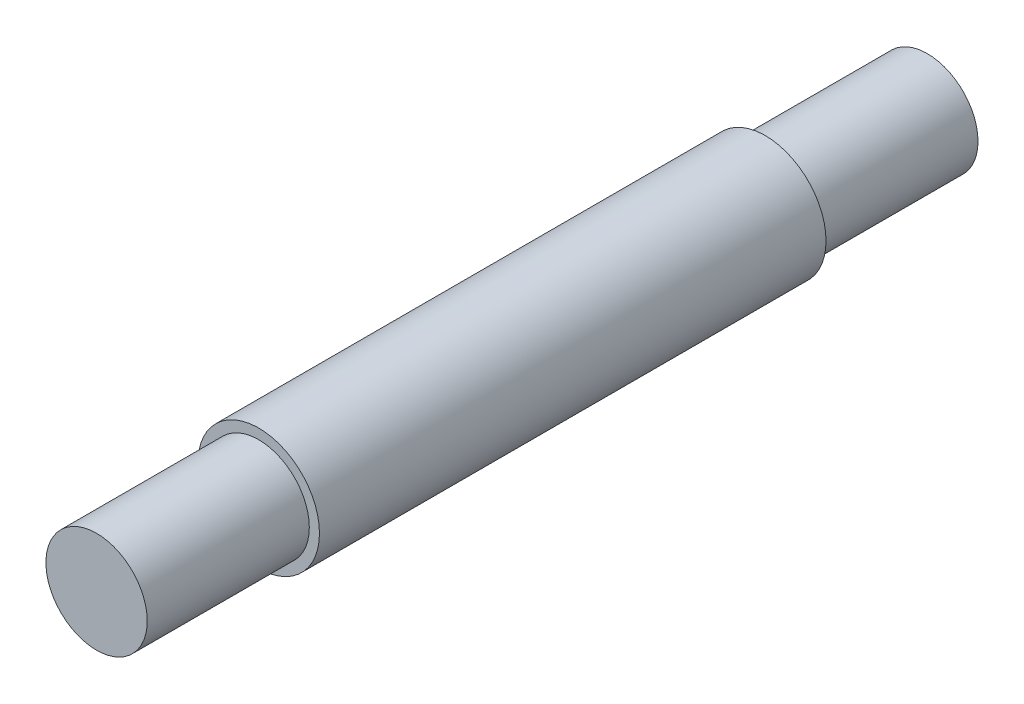
SolidWorks part; units mm, degrees
ref_plane "Ön Düzlem" through (0, 0, 0) normal (0, 0, 1) x (1, 0, 0)
ref_plane "Üst Düzlem" through (0, 0, 0) normal (0, 1, 0) x (1, 0, 0)
ref_plane "Sağ Düzlem" through (0, 0, 0) normal (1, 0, 0) x (0, 0, -1)
sketch "Çizim1" plane through (0, 0, 0) normal (1, 0, 0) x (0, 0, -1)
  line L0 (3.2754, 16.6168) -> (19.2754, 16.6168)
  line L1 (-46.7246, 17.6168) -> (3.2754, 17.6168)
  line L2 (-46.7246, 17.6168) -> (-46.7246, 16.6168)
  line L4 (3.2754, 17.6168) -> (3.2754, 16.6168)
  line L5 (-62.7246, 16.6168) -> (-46.7246, 16.6168)
  line L6 (-62.7246, 16.6168) -> (-62.7246, 11.6168)
  line L7 (-62.7246, 11.6168) -> (19.2754, 11.6168)
  line L8 (19.2754, 16.6168) -> (19.2754, 11.6168)
  dimension "D1" = 50
  dimension "D2" = 82
  dimension "D3" = 16
  dimension "D4" = 5
  dimension "D5" = 6
revolve "Döndür2" add sketch "Çizim1" angle 360 about L7
